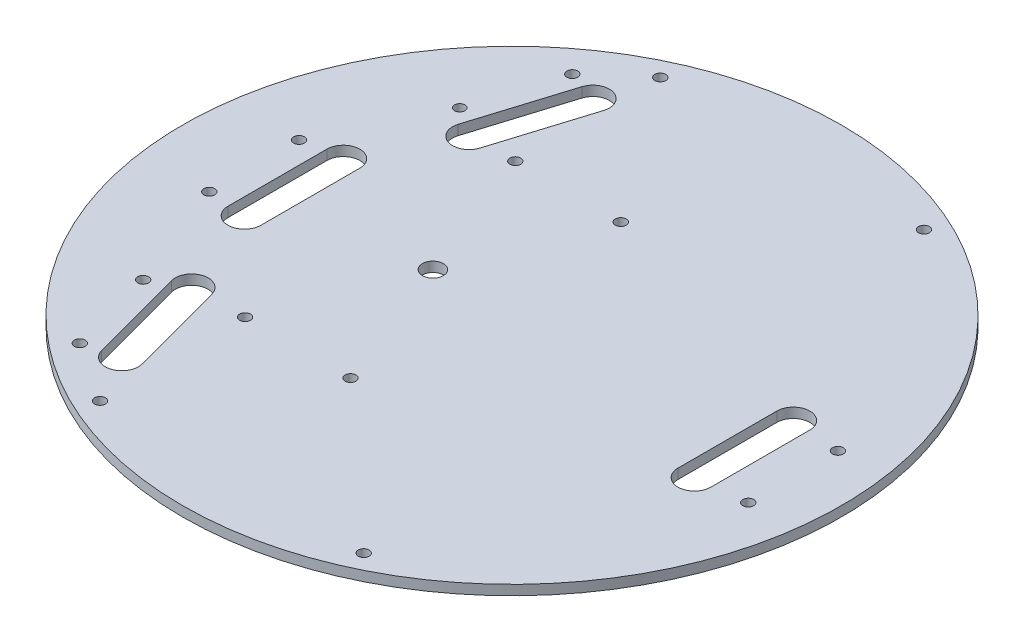
SolidWorks part; units mm, degrees
ref_plane "Alzado" through (0, 0, 0) normal (0, 0, 1) x (1, 0, 0)
ref_plane "Planta" through (0, 0, 0) normal (0, 1, 0) x (1, 0, 0)
ref_plane "Vista lateral" through (0, 0, 0) normal (1, 0, 0) x (0, 0, -1)
sketch "Croquis1" plane through (0, 0, 0) normal (0, 1, 0) x (1, 0, 0)
  line L0 (0, 0) -> (-88.4646, 0) construction
  line L1 (-88.4646, 0) -> (-72.2, -60.7004) construction
  line L5 (-88.4646, 0) -> (-88.4646, -58.7493) construction
  line L6 (-88.0486, -1.5529) -> (-72.2, 49.51) construction
  line L8 (-72.2, 15.6777) -> (-72.2, -15.7875) construction
  line L10 (0, 0) -> (0, -71.6257) construction
  line L12 (72.2, 15.6777) -> (72.2, -15.7875) construction
  line L13 (-55.9252, -41.2536) -> (-48.1607, -70.2313) construction
  line L14 (-51.0956, -39.9595) -> (-43.331, -68.9372)
  line L15 (-60.7549, -42.5476) -> (-52.9903, -71.5254)
  line L16 (-66.7543, 15.5777) -> (-66.7543, -14.4223) construction
  line L17 (-61.7543, 15.5777) -> (-61.7543, -14.4223)
  line L18 (-71.7543, 15.5777) -> (-71.7543, -14.4223)
  line L19 (-44.6931, 69.2155) -> (-53.5858, 40.5638) construction
  line L20 (-39.9178, 67.7334) -> (-48.8105, 39.0817)
  line L21 (-49.4684, 70.6977) -> (-58.3611, 42.046)
  line L22 (70.3378, 15.0228) -> (70.3378, -14.9772) construction
  line L23 (75.3378, 15.0228) -> (75.3378, -14.9772)
  line L24 (65.3378, 15.0228) -> (65.3378, -14.9772)
  circle A15 centre (40, -85) radius 1.65
  circle A16 centre (40, 85) radius 1.65
  circle A19 centre (0, 0) radius 100
  circle A25 centre (-40, -85) radius 1.65
  circle A28 centre (-40, 85) radius 1.65
  circle A29 centre (-40, 41) radius 1.65
  circle A30 centre (-40, -41) radius 1.65
  circle A31 centre (-24, 0) radius 3.175
  circle A32 centre (-8, 41) radius 1.65
  circle A33 centre (-8, -41) radius 1.65
  circle A34 centre (85.0702, 13.8244) radius 1.65
  circle A36 centre (85.0702, -13.3756) radius 1.65
  circle A38 centre (-54.2275, 72.5284) radius 1.65
  circle A39 centre (-62.4567, 46.6031) radius 1.5598
  circle A40 centre (-78.397, 13.7523) radius 1.65
  circle A41 centre (-78.397, -13.4477) radius 1.65
  circle A42 centre (-65.2783, -46.6361) radius 1.65
  circle A43 centre (-58.2384, -72.9093) radius 1.65
  arc A44 (-51.0956, -39.9595) -> (-60.7549, -42.5476) centre (-55.9252, -41.2536) ccw
  arc A45 (-52.9903, -71.5254) -> (-43.331, -68.9372) centre (-48.1607, -70.2313) ccw
  arc A46 (-61.7543, 15.5777) -> (-71.7543, 15.5777) centre (-66.7543, 15.5777) ccw
  arc A47 (-71.7543, -14.4223) -> (-61.7543, -14.4223) centre (-66.7543, -14.4223) ccw
  arc A48 (-39.9178, 67.7334) -> (-49.4684, 70.6977) centre (-44.6931, 69.2155) ccw
  arc A49 (-58.3611, 42.046) -> (-48.8105, 39.0817) centre (-53.5858, 40.5638) ccw
  arc A50 (75.3378, 15.0228) -> (65.3378, 15.0228) centre (70.3378, 15.0228) ccw
  arc A51 (65.3378, -14.9772) -> (75.3378, -14.9772) centre (70.3378, -14.9772) ccw
  point P17 (0, 0)
  point P48 (-52.043, -55.7424)
  point P57 (-66.7543, 0.5777)
  point P64 (-49.1394, 54.8897)
  point P69 (0, 0)
  point P72 (0, 0)
  point P73 (70.3378, 0.0228)
  dimension "D10" = 200
  dimension "D14" = 41
  dimension "D3" = 40
  dimension "D7" = 3.3
  dimension "D13" = 24
  dimension "D16" = 41
  dimension "D2" = 85
  dimension "D18" = 8
  dimension "D24" = 10
  dimension "D26" = 10
  dimension "D5" = 40
  dimension "D12" = 6.35
  dimension "D4" = 85
  dimension "D6" = 40
  dimension "D8" = 40
  dimension "D9" = 85
  dimension "D11" = 85
  dimension "D15" = 41
  dimension "D17" = 41
  dimension "D19" = 15
  dimension "D20" = 30
  dimension "D21" = 30
  dimension "D22" = 30
  dimension "D23" = 197.243
  dimension "D25" = 10
extrude "Saliente-Extruir1" add sketch "Croquis1" along normal blind 3
